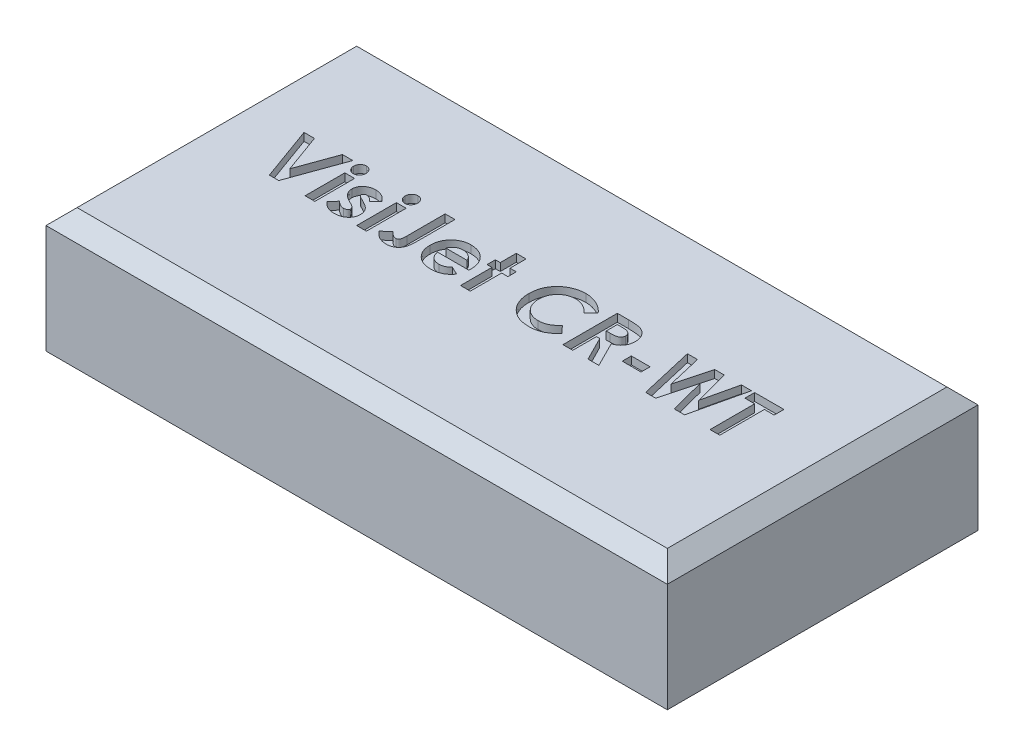
SolidWorks part; units mm, degrees
ref_plane "Front Plane" through (0, 0, 0) normal (0, 0, 1) x (1, 0, 0)
ref_plane "Top Plane" through (0, 0, 0) normal (0, 1, 0) x (1, 0, 0)
ref_plane "Right Plane" through (0, 0, 0) normal (1, 0, 0) x (0, 0, -1)
sketch "Sketch1" plane through (0, 0, 0) normal (0, 1, 0) x (1, 0, 0)
  line L1 (-20, -7.6815) -> (20, -7.6815)
  line L2 (-20, -7.6815) -> (-20, 12.3185)
  line L3 (-20, 12.3185) -> (20, 12.3185)
  line L4 (20, -7.6815) -> (20, 12.3185)
  line L5 (-20, -7.6815) -> (20, 12.3185) construction
  line L6 (-20, 12.3185) -> (20, -7.6815) construction
  point P0 (0, 2.3185)
  dimension "D1" = 40
  dimension "D2" = 20
extrude "Boss-Extrude1" add sketch "Sketch1" along normal blind 8
chamfer "Chamfer1" distance 1 angle 45 4 edges at (0, 8, 7.6815) (-20, 8, -2.3185) (0, 8, -12.3185) (20, 8, -2.3185)
sketch "Sketch2" plane through (0, 8, 0) normal (0, 1, 0) x (1, 0, 0)
  line L0 (-19, 11.3185) -> (-19, -6.6815) construction
  line L2 (-19, -6.6815) -> (19, -6.6815) construction
  text T0 "<b>VisiJet CR-WT</b>"
  dimension "D1" = 3
  dimension "D2" = 8
extrude "Cut-Extrude1" cut sketch "Sketch2" against normal blind 0.5
